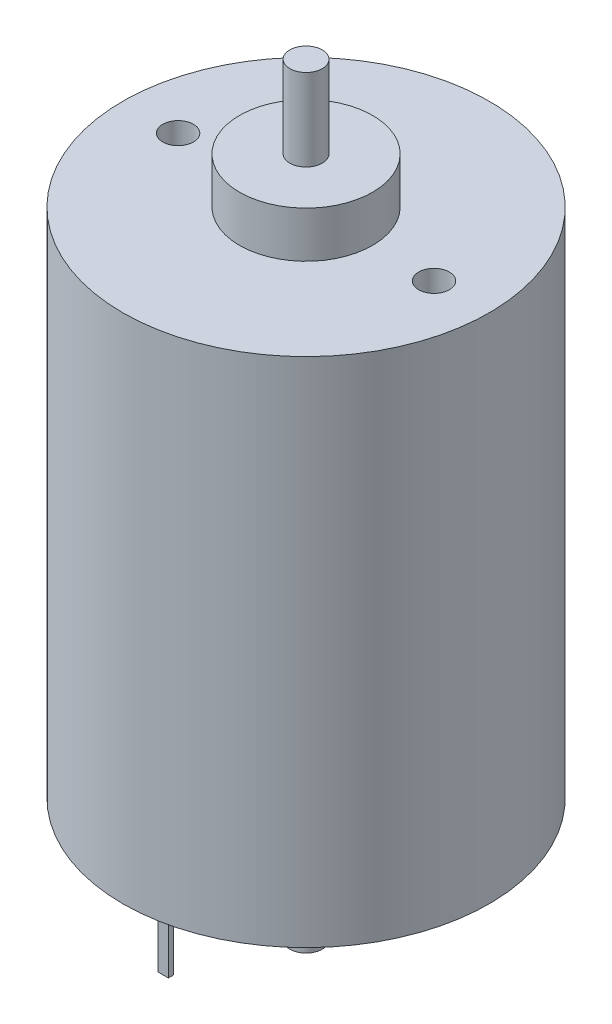
SolidWorks part; units mm, degrees
material "Plain Carbon Steel"
ref_plane "Front Plane" through (0, 0, 0) normal (0, 0, 1) x (1, 0, 0)
ref_plane "Top Plane" through (0, 0, 0) normal (0, 1, 0) x (1, 0, 0)
ref_plane "Right Plane" through (0, 0, 0) normal (1, 0, 0) x (0, 0, -1)
sketch "Sketch1" plane through (0, 0, 0) normal (0, 1, 0) x (1, 0, 0)
  circle A0 centre (0, 0) radius 17.9
extrude "Boss-Extrude1" add sketch "Sketch1" along normal blind 50
sketch "Sketch2" plane through (0, 50, 0) normal (0, 1, 0) x (1, 0, 0)
  circle A0 centre (0, 0) radius 6.5
extrude "Boss-Extrude2" add sketch "Sketch2" along normal blind 4.5
sketch "Sketch3" plane through (0, 54.5, 0) normal (0, 1, 0) x (1, 0, 0)
  circle A0 centre (0, 0) radius 1.585
extrude "Boss-Extrude3" add sketch "Sketch3" along normal blind 12.5
sketch "Sketch4" plane through (0, 0, 0) normal (0, -1, 0) x (1, 0, 0)
  circle A0 centre (0, 0) radius 5.1
extrude "Boss-Extrude4" add sketch "Sketch4" along normal blind 3
sketch "Sketch5" plane through (0, -3, 0) normal (0, -1, 0) x (-1, 0, 0)
  circle A0 centre (0, 0) radius 1.585
extrude "Boss-Extrude5" add sketch "Sketch5" along normal blind 12.5
sketch "Sketch6" plane through (0, 0, 0) normal (0, -1, 0) x (1, 0, 0)
  line L0 (0, 0) -> (0, -17.9)
  line L2 (0, -13.7) -> (0, -13.95)
  line L3 (0, -13.95) -> (-0.5, -13.95)
  line L4 (-0.5, -13.95) -> (0.5, -13.95)
  line L5 (0.5, -13.95) -> (0.5, -13.45)
  line L6 (0.5, -13.45) -> (-0.5, -13.45)
  line L7 (-0.5, -13.45) -> (-0.5, -13.95)
  line L8 (0, 13.7) -> (0, 12.8825)
  line L9 (0, 0) -> (-17.9, 0)
  line L10 (-17.9, 0) -> (17.9, 0)
  line L11 (-0.5, 13.45) -> (-0.5, 13.95)
  line L12 (0.5, 13.45) -> (-0.5, 13.45)
  line L13 (0.5, 13.95) -> (0.5, 13.45)
  line L14 (-0.5, 13.95) -> (0.5, 13.95)
  line L15 (0, 13.95) -> (-0.5, 13.95)
  line L16 (0, 13.7) -> (0, 13.95)
  circle A0 centre (0, 0) radius 17.9 construction
extrude "Boss-Extrude6" add sketch "Sketch6" along normal blind 8 contours L6 L7 L3 L0 | L5 L6 L0 L4 | L8 L16 L14 L11 L12 | L16 L8 L12 L13 L14
sketch "Sketch7" plane through (0, 50, 0) normal (0, 1, 0) x (1, 0, 0)
  line L0 (-12.5, 0) -> (12.5, 0)
  circle A0 centre (0, 0) radius 12.5
  circle A1 centre (12.5, 0) radius 1.5
  circle A2 centre (-12.5, 0) radius 1.5
extrude "Cut-Extrude1" cut sketch "Sketch7" against normal blind 8 contours A0 A1 | L0 A1 A0 | A0 A1 L0 | A0 A2 L0 | L0 A2 A0 | A0 A2
sketch "Sketch8" plane through (0, 67, 0) normal (0, 1, 0) x (1, 0, 0)
  circle A1 centre (0, 0) radius 1.585
  circle A2 centre (0, 0) radius 1.585
  dimension "D1" = 0
extrude "Cut-Extrude2" cut sketch "Sketch8" against normal blind 4.5
sketch "Sketch9" plane through (0, -15.5, 0) normal (0, -1, 0) x (1, 0, 0)
  circle A1 centre (0, 0) radius 1.585
  circle A2 centre (0, 0) radius 1.585
  dimension "D1" = 0
extrude "Cut-Extrude3" cut sketch "Sketch9" against normal blind 3.5
